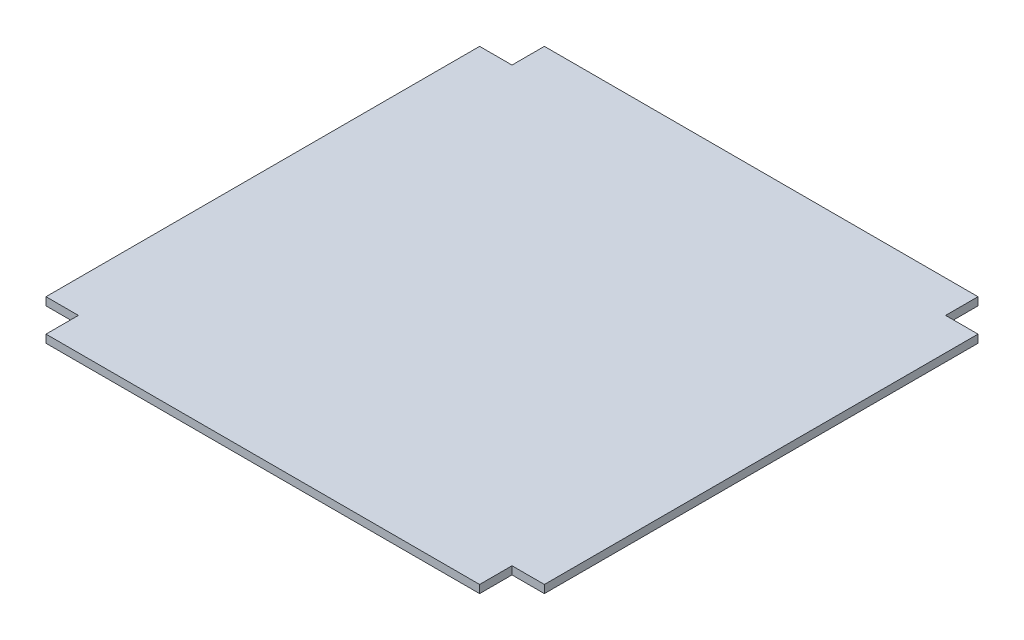
SolidWorks part; units mm, degrees
ref_plane "Front Plane" through (0, 0, 0) normal (0, 0, 1) x (1, 0, 0)
ref_plane "Top Plane" through (0, 0, 0) normal (0, 1, 0) x (1, 0, 0)
ref_plane "Right Plane" through (0, 0, 0) normal (1, 0, 0) x (0, 0, -1)
sketch "Sketch1" plane through (0, 0, 0) normal (0, 1, 0) x (1, 0, 0)
  line L0 (0, 0) -> (50, 0) construction
  line L1 (0, 0) -> (0, 50) construction
  line L3 (0, 0) -> (0, -50) construction
  line L4 (0, 0) -> (-50, 0) construction
  line L5 (0, -55) -> (0, 55) construction
  line L6 (-50, 50) -> (50, 50)
  line L7 (-50, 50) -> (-50, -50)
  line L8 (-50, -50) -> (50, -50)
  line L9 (50, 50) -> (50, -50)
  line L10 (-50, 50) -> (-43.5, 50)
  line L11 (-50, 50) -> (-50, 43.5)
  line L12 (-50, 43.5) -> (-43.5, 43.5)
  line L13 (-43.5, 50) -> (-43.5, 43.5)
  line L14 (50, 43.5) -> (43.5, 43.5)
  line L15 (43.5, 50) -> (43.5, 43.5)
  line L16 (50, 50) -> (43.5, 50)
  line L17 (50, 50) -> (50, 43.5)
  line L18 (-55, 0) -> (55, 0) construction
  line L19 (50, -50) -> (43.5, -50)
  line L20 (43.5, -50) -> (43.5, -43.5)
  line L21 (50, -43.5) -> (43.5, -43.5)
  line L22 (50, -50) -> (50, -43.5)
  line L23 (-50, -43.5) -> (-43.5, -43.5)
  line L24 (-43.5, -50) -> (-43.5, -43.5)
  line L25 (-50, -50) -> (-43.5, -50)
  line L26 (-50, -50) -> (-50, -43.5)
  dimension "D1" = 4
extrude "Boss-Extrude1" add sketch "Sketch1" along normal blind 1.6 contours L24 L8 L20 L21 L9 L14 L15 L6 L13 L12 L7 L23
